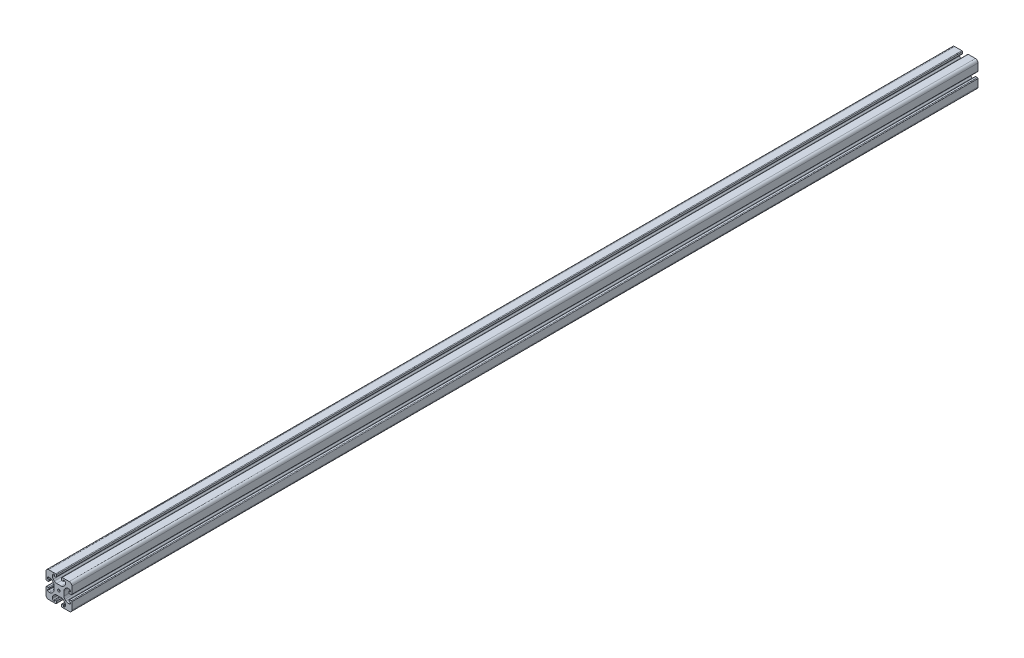
SolidWorks part; units mm, degrees
material "氧化铝"
ref_plane "前视基准面" through (0, 0, 0) normal (0, 0, 1) x (1, 0, 0)
ref_plane "上视基准面" through (0, 0, 0) normal (0, 1, 0) x (1, 0, 0)
ref_plane "右视基准面" through (0, 0, 0) normal (1, 0, 0) x (0, 0, -1)
sketch "Model" plane through (0, 0, 0) normal (0, 0, 1) x (1, 0, 0)
  line L2 (3038.626, 1538.5549) -> (3045.7412, 1538.5549)
  line L3 (3037.1836, 1526.3047) -> (3026.1835, 1526.3048)
  line L4 (3032.1835, 1530.8048) -> (3032.1835, 1532.1123)
  line L5 (3033.6481, 1535.6478) -> (3035.0903, 1537.0902)
  line L6 (3034.7336, 1528.3048) -> (3034.6836, 1528.3048)
  line L7 (3037.1836, 1530.8048) -> (3035.6835, 1530.8048)
  line L8 (3035.1835, 1528.7549) -> (3035.1835, 1530.3049)
  line L9 (3022.1835, 1530.305) -> (3022.1835, 1541.3049)
  line L10 (3038.1835, 1565.3049) -> (3038.1835, 1562.8049)
  line L11 (3031.5267, 1554.8404) -> (3032.9691, 1553.398)
  line L12 (3026.6837, 1556.305) -> (3027.9911, 1556.305)
  line L13 (3026.1835, 1553.305) -> (3024.6335, 1553.305)
  line L14 (3024.1836, 1553.7549) -> (3024.1836, 1553.8049)
  line L15 (3026.6837, 1551.3049) -> (3026.6837, 1552.805)
  line L16 (3023.1837, 1550.305) -> (3025.6835, 1550.305)
  line L17 (3022.1835, 1562.3048) -> (3022.1835, 1551.3049)
  line L18 (3023.1837, 1542.3048) -> (3025.6835, 1542.3048)
  line L19 (3026.6837, 1541.3049) -> (3026.6837, 1539.8048)
  line L20 (3024.1836, 1538.8549) -> (3024.1836, 1538.8048)
  line L21 (3026.1835, 1539.3048) -> (3024.6335, 1539.3048)
  line L22 (3026.6837, 1536.3048) -> (3027.9911, 1536.3048)
  line L23 (3031.5267, 1537.7694) -> (3032.9691, 1539.2118)
  line L24 (3035.1835, 1563.8549) -> (3035.1835, 1562.3049)
  line L25 (3037.1836, 1561.805) -> (3035.6835, 1561.805)
  line L26 (3034.7336, 1564.305) -> (3034.6836, 1564.305)
  line L27 (3038.1835, 1527.3048) -> (3038.1835, 1529.8049)
  line L28 (3049.9338, 1549.8624) -> (3049.9338, 1542.7473)
  line L29 (3047.1836, 1566.3051) -> (3058.1838, 1566.305)
  line L30 (3052.1837, 1561.805) -> (3052.1837, 1560.4975)
  line L31 (3050.7191, 1556.962) -> (3049.2769, 1555.5195)
  line L32 (3033.6481, 1556.962) -> (3035.0903, 1555.5195)
  line L33 (3032.1835, 1561.805) -> (3032.1835, 1560.4975)
  line L34 (3046.1837, 1527.3048) -> (3046.1837, 1529.8049)
  line L35 (3049.6336, 1564.305) -> (3049.6837, 1564.305)
  line L36 (3047.1836, 1561.805) -> (3048.6837, 1561.805)
  line L37 (3049.1837, 1563.8549) -> (3049.1837, 1562.3049)
  line L38 (3052.8406, 1537.7694) -> (3051.3981, 1539.2118)
  line L39 (3057.6836, 1536.3048) -> (3056.3761, 1536.3048)
  line L40 (3058.1838, 1539.3048) -> (3059.7337, 1539.3048)
  line L41 (3060.1836, 1538.8549) -> (3060.1836, 1538.8048)
  line L42 (3057.6836, 1541.3049) -> (3057.6836, 1539.8048)
  line L43 (3061.1835, 1542.3048) -> (3058.6837, 1542.3048)
  line L44 (3037.1836, 1566.3051) -> (3026.1835, 1566.305)
  line L45 (3062.1837, 1562.3048) -> (3062.1837, 1551.3049)
  line L46 (3038.626, 1554.0549) -> (3045.7412, 1554.0549)
  line L47 (3061.1835, 1550.305) -> (3058.6837, 1550.305)
  line L48 (3057.6836, 1551.3049) -> (3057.6836, 1552.805)
  line L49 (3060.1836, 1553.7549) -> (3060.1836, 1553.8049)
  line L50 (3058.1838, 1553.305) -> (3059.7337, 1553.305)
  line L51 (3057.6836, 1556.305) -> (3056.3761, 1556.305)
  line L52 (3034.4335, 1549.8624) -> (3034.4335, 1542.7473)
  line L53 (3052.8406, 1554.8404) -> (3051.3981, 1553.398)
  line L54 (3046.1837, 1565.3049) -> (3046.1837, 1562.8049)
  line L55 (3062.1837, 1530.305) -> (3062.1837, 1541.3049)
  line L56 (3049.1837, 1528.7549) -> (3049.1837, 1530.3049)
  line L57 (3047.1836, 1530.8048) -> (3048.6837, 1530.8048)
  line L58 (3049.6336, 1528.3048) -> (3049.6837, 1528.3048)
  line L59 (3050.7191, 1535.6478) -> (3049.2769, 1537.0902)
  line L60 (3052.1837, 1530.8048) -> (3052.1837, 1532.1123)
  line L61 (3047.1836, 1526.3047) -> (3058.1838, 1526.3048)
  spline S0 degree 3 poles (3026.1835, 1526.3048) (3024.8345, 1526.3048) (3023.0907, 1527.3653) (3022.1835, 1529.3623) (3022.1835, 1530.305) knots 0 0 0 0 0.550544 1 1 1 1
  spline S1 degree 3 poles (3032.1835, 1532.1123) (3032.1835, 1532.8016) (3032.4749, 1534.0839) (3033.1746, 1535.1743) (3033.6481, 1535.6478) knots 0 0 0 0 0.510204 1 1 1 1
  spline S2 degree 3 poles (3035.0903, 1537.0902) (3035.5565, 1537.5565) (3036.6626, 1538.2661) (3037.9261, 1538.5549) (3038.626, 1538.5549) knots 0 0 0 0 0.489373 1 1 1 1
  spline S3 degree 3 poles (3038.1835, 1529.8049) (3038.1835, 1530.1088) (3037.8896, 1530.5989) (3037.4374, 1530.8048) (3037.1836, 1530.8048) knots 0 0 0 0 0.565195 1 1 1 1
  spline S4 degree 3 poles (3035.6835, 1530.8048) (3035.5526, 1530.8048) (3035.3033, 1530.6873) (3035.1835, 1530.4632) (3035.1835, 1530.3049) knots 0 0 0 0 0.482406 1 1 1 1
  spline S5 degree 3 poles (3035.1835, 1528.7549) (3035.1835, 1528.6211) (3035.0566, 1528.3999) (3034.8531, 1528.3048) (3034.7336, 1528.3048) knots 0 0 0 0 0.549542 1 1 1 1
  spline S6 degree 3 poles (3034.6836, 1528.3048) (3033.9863, 1528.3048) (3032.7434, 1528.9085) (3032.1835, 1530.0457) (3032.1835, 1530.8048) knots 0 0 0 0 0.502794 1 1 1 1
  spline S7 degree 3 poles (3022.1835, 1541.3049) (3022.1835, 1541.6421) (3022.4486, 1542.0781) (3022.9479, 1542.3048) (3023.1837, 1542.3048) knots 0 0 0 0 0.550415 1 1 1 1
  spline S8 degree 3 poles (3025.6835, 1542.3048) (3026.0194, 1542.3048) (3026.4561, 1542.0413) (3026.6837, 1541.5421) (3026.6837, 1541.3049) knots 0 0 0 0 0.548464 1 1 1 1
  spline S9 degree 3 poles (3026.6837, 1539.8048) (3026.6837, 1539.6386) (3026.5536, 1539.4195) (3026.3039, 1539.3048) (3026.1835, 1539.3048) knots 0 0 0 0 0.543008 1 1 1 1
  spline S10 degree 3 poles (3024.6335, 1539.3048) (3024.4666, 1539.3048) (3024.2778, 1539.1702) (3024.1836, 1538.9461) (3024.1836, 1538.8549) knots 0 0 0 0 0.601272 1 1 1 1
  spline S11 degree 3 poles (3024.1836, 1538.8048) (3024.1836, 1537.973) (3024.8335, 1536.8769) (3026.0817, 1536.3048) (3026.6837, 1536.3048) knots 0 0 0 0 0.543506 1 1 1 1
  spline S12 degree 3 poles (3027.9911, 1536.3048) (3028.6698, 1536.3048) (3029.9377, 1536.5775) (3031.0429, 1537.2857) (3031.5267, 1537.7694) knots 0 0 0 0 0.495307 1 1 1 1
  spline S13 degree 3 poles (3032.9691, 1539.2118) (3033.4334, 1539.6761) (3034.1274, 1540.7681) (3034.4335, 1542.0508) (3034.4335, 1542.7473) knots 0 0 0 0 0.481772 1 1 1 1
  spline S14 degree 3 poles (3037.1836, 1526.3047) (3037.4, 1526.3047) (3037.8987, 1526.5226) (3038.1835, 1526.9491) (3038.1835, 1527.3048) knots 0 0 0 0 0.421049 1 1 1 1
  spline S15 degree 3 poles (3058.1838, 1566.305) (3059.5327, 1566.305) (3061.2765, 1565.2445) (3062.1837, 1563.2474) (3062.1837, 1562.3048) knots 0 0 0 0 0.550544 1 1 1 1
  spline S16 degree 3 poles (3052.1837, 1560.4975) (3052.1837, 1559.8082) (3051.8923, 1558.5259) (3051.1926, 1557.4355) (3050.7191, 1556.962) knots 0 0 0 0 0.510204 1 1 1 1
  spline S17 degree 3 poles (3049.2769, 1555.5195) (3048.8108, 1555.0533) (3047.7046, 1554.3437) (3046.4411, 1554.0549) (3045.7412, 1554.0549) knots 0 0 0 0 0.489373 1 1 1 1
  spline S18 degree 3 poles (3046.1837, 1562.8049) (3046.1837, 1562.501) (3046.4776, 1562.0109) (3046.9298, 1561.805) (3047.1836, 1561.805) knots 0 0 0 0 0.565195 1 1 1 1
  spline S19 degree 3 poles (3037.1836, 1566.3051) (3037.4, 1566.3051) (3037.8987, 1566.0872) (3038.1835, 1565.6607) (3038.1835, 1565.3049) knots 0 0 0 0 0.421049 1 1 1 1
  spline S20 degree 3 poles (3048.6837, 1561.805) (3048.8146, 1561.805) (3049.0639, 1561.9225) (3049.1837, 1562.1466) (3049.1837, 1562.3049) knots 0 0 0 0 0.482406 1 1 1 1
  spline S21 degree 3 poles (3032.9691, 1553.398) (3033.4334, 1552.9336) (3034.1274, 1551.8416) (3034.4335, 1550.559) (3034.4335, 1549.8624) knots 0 0 0 0 0.481772 1 1 1 1
  spline S22 degree 3 poles (3027.9911, 1556.305) (3028.6698, 1556.305) (3029.9377, 1556.0322) (3031.0429, 1555.3241) (3031.5267, 1554.8404) knots 0 0 0 0 0.495307 1 1 1 1
  spline S23 degree 3 poles (3024.1836, 1553.8049) (3024.1836, 1554.6368) (3024.8335, 1555.7328) (3026.0817, 1556.305) (3026.6837, 1556.305) knots 0 0 0 0 0.543506 1 1 1 1
  spline S24 degree 3 poles (3024.6335, 1553.305) (3024.4666, 1553.305) (3024.2778, 1553.4396) (3024.1836, 1553.6637) (3024.1836, 1553.7549) knots 0 0 0 0 0.601272 1 1 1 1
  spline S25 degree 3 poles (3026.6837, 1552.805) (3026.6837, 1552.9712) (3026.5536, 1553.1903) (3026.3039, 1553.305) (3026.1835, 1553.305) knots 0 0 0 0 0.543008 1 1 1 1
  spline S26 degree 3 poles (3025.6835, 1550.305) (3026.0194, 1550.305) (3026.4561, 1550.5685) (3026.6837, 1551.0677) (3026.6837, 1551.3049) knots 0 0 0 0 0.548464 1 1 1 1
  spline S27 degree 3 poles (3022.1835, 1551.3049) (3022.1835, 1550.9677) (3022.4486, 1550.5317) (3022.9479, 1550.305) (3023.1837, 1550.305) knots 0 0 0 0 0.550415 1 1 1 1
  spline S28 degree 3 poles (3049.1837, 1563.8549) (3049.1837, 1563.9886) (3049.3106, 1564.2099) (3049.5141, 1564.305) (3049.6336, 1564.305) knots 0 0 0 0 0.549542 1 1 1 1
  spline S29 degree 3 poles (3049.6837, 1564.305) (3050.3809, 1564.305) (3051.6238, 1563.7012) (3052.1837, 1562.5641) (3052.1837, 1561.805) knots 0 0 0 0 0.502794 1 1 1 1
  spline S30 degree 3 poles (3062.1837, 1551.3049) (3062.1837, 1550.9677) (3061.9186, 1550.5317) (3061.4193, 1550.305) (3061.1835, 1550.305) knots 0 0 0 0 0.550415 1 1 1 1
  spline S31 degree 3 poles (3058.6837, 1550.305) (3058.3478, 1550.305) (3057.9111, 1550.5685) (3057.6836, 1551.0677) (3057.6836, 1551.3049) knots 0 0 0 0 0.548464 1 1 1 1
  spline S32 degree 3 poles (3057.6836, 1552.805) (3057.6836, 1552.9712) (3057.8136, 1553.1903) (3058.0633, 1553.305) (3058.1838, 1553.305) knots 0 0 0 0 0.543008 1 1 1 1
  spline S33 degree 3 poles (3059.7337, 1553.305) (3059.9006, 1553.305) (3060.0894, 1553.4396) (3060.1836, 1553.6637) (3060.1836, 1553.7549) knots 0 0 0 0 0.601272 1 1 1 1
  spline S34 degree 3 poles (3060.1836, 1553.8049) (3060.1836, 1554.6368) (3059.5337, 1555.7328) (3058.2856, 1556.305) (3057.6836, 1556.305) knots 0 0 0 0 0.543506 1 1 1 1
  spline S35 degree 3 poles (3056.3761, 1556.305) (3055.6974, 1556.305) (3054.4295, 1556.0322) (3053.3243, 1555.3241) (3052.8406, 1554.8404) knots 0 0 0 0 0.495307 1 1 1 1
  spline S36 degree 3 poles (3051.3981, 1553.398) (3050.9338, 1552.9336) (3050.2398, 1551.8416) (3049.9338, 1550.559) (3049.9338, 1549.8624) knots 0 0 0 0 0.481772 1 1 1 1
  spline S37 degree 3 poles (3047.1836, 1566.3051) (3046.9672, 1566.3051) (3046.4685, 1566.0872) (3046.1837, 1565.6607) (3046.1837, 1565.3049) knots 0 0 0 0 0.421049 1 1 1 1
  spline S38 degree 3 poles (3034.6836, 1564.305) (3033.9863, 1564.305) (3032.7434, 1563.7012) (3032.1835, 1562.5641) (3032.1835, 1561.805) knots 0 0 0 0 0.502794 1 1 1 1
  spline S39 degree 3 poles (3035.1835, 1563.8549) (3035.1835, 1563.9886) (3035.0566, 1564.2099) (3034.8531, 1564.305) (3034.7336, 1564.305) knots 0 0 0 0 0.549542 1 1 1 1
  spline S40 degree 3 poles (3035.6835, 1561.805) (3035.5526, 1561.805) (3035.3033, 1561.9225) (3035.1835, 1562.1466) (3035.1835, 1562.3049) knots 0 0 0 0 0.482406 1 1 1 1
  spline S41 degree 3 poles (3038.1835, 1562.8049) (3038.1835, 1562.501) (3037.8896, 1562.0109) (3037.4374, 1561.805) (3037.1836, 1561.805) knots 0 0 0 0 0.565195 1 1 1 1
  spline S42 degree 3 poles (3047.1836, 1526.3047) (3046.9672, 1526.3047) (3046.4685, 1526.5226) (3046.1837, 1526.9491) (3046.1837, 1527.3048) knots 0 0 0 0 0.421049 1 1 1 1
  spline S43 degree 3 poles (3051.3981, 1539.2118) (3050.9338, 1539.6761) (3050.2398, 1540.7681) (3049.9338, 1542.0508) (3049.9338, 1542.7473) knots 0 0 0 0 0.481772 1 1 1 1
  spline S44 degree 3 poles (3056.3761, 1536.3048) (3055.6974, 1536.3048) (3054.4295, 1536.5775) (3053.3243, 1537.2857) (3052.8406, 1537.7694) knots 0 0 0 0 0.495307 1 1 1 1
  spline S45 degree 3 poles (3060.1836, 1538.8048) (3060.1836, 1537.973) (3059.5337, 1536.8769) (3058.2856, 1536.3048) (3057.6836, 1536.3048) knots 0 0 0 0 0.543506 1 1 1 1
  spline S46 degree 3 poles (3059.7337, 1539.3048) (3059.9006, 1539.3048) (3060.0894, 1539.1702) (3060.1836, 1538.9461) (3060.1836, 1538.8549) knots 0 0 0 0 0.601272 1 1 1 1
  spline S47 degree 3 poles (3057.6836, 1539.8048) (3057.6836, 1539.6386) (3057.8136, 1539.4195) (3058.0633, 1539.3048) (3058.1838, 1539.3048) knots 0 0 0 0 0.543008 1 1 1 1
  spline S48 degree 3 poles (3058.6837, 1542.3048) (3058.3478, 1542.3048) (3057.9111, 1542.0413) (3057.6836, 1541.5421) (3057.6836, 1541.3049) knots 0 0 0 0 0.548464 1 1 1 1
  spline S49 degree 3 poles (3062.1837, 1541.3049) (3062.1837, 1541.6421) (3061.9186, 1542.0781) (3061.4193, 1542.3048) (3061.1835, 1542.3048) knots 0 0 0 0 0.550415 1 1 1 1
  spline S50 degree 3 poles (3049.6837, 1528.3048) (3050.3809, 1528.3048) (3051.6238, 1528.9085) (3052.1837, 1530.0457) (3052.1837, 1530.8048) knots 0 0 0 0 0.502794 1 1 1 1
  spline S51 degree 3 poles (3035.0903, 1555.5195) (3035.5565, 1555.0533) (3036.6626, 1554.3437) (3037.9261, 1554.0549) (3038.626, 1554.0549) knots 0 0 0 0 0.489373 1 1 1 1
  spline S52 degree 3 poles (3032.1835, 1560.4975) (3032.1835, 1559.8082) (3032.4749, 1558.5259) (3033.1746, 1557.4355) (3033.6481, 1556.962) knots 0 0 0 0 0.510204 1 1 1 1
  spline S53 degree 3 poles (3049.1837, 1528.7549) (3049.1837, 1528.6211) (3049.3106, 1528.3999) (3049.5141, 1528.3048) (3049.6336, 1528.3048) knots 0 0 0 0 0.549542 1 1 1 1
  spline S54 degree 3 poles (3048.6837, 1530.8048) (3048.8146, 1530.8048) (3049.0639, 1530.6873) (3049.1837, 1530.4632) (3049.1837, 1530.3049) knots 0 0 0 0 0.482406 1 1 1 1
  spline S55 degree 3 poles (3046.1837, 1529.8049) (3046.1837, 1530.1088) (3046.4776, 1530.5989) (3046.9298, 1530.8048) (3047.1836, 1530.8048) knots 0 0 0 0 0.565195 1 1 1 1
  spline S56 degree 3 poles (3049.2769, 1537.0902) (3048.8108, 1537.5565) (3047.7046, 1538.2661) (3046.4411, 1538.5549) (3045.7412, 1538.5549) knots 0 0 0 0 0.489373 1 1 1 1
  spline S57 degree 3 poles (3052.1837, 1532.1123) (3052.1837, 1532.8016) (3051.8923, 1534.0839) (3051.1926, 1535.1743) (3050.7191, 1535.6478) knots 0 0 0 0 0.510204 1 1 1 1
  spline S58 degree 3 poles (3058.1838, 1526.3048) (3059.5327, 1526.3048) (3061.2765, 1527.3653) (3062.1837, 1529.3623) (3062.1837, 1530.305) knots 0 0 0 0 0.550544 1 1 1 1
  spline S68 degree 3 poles (3026.1835, 1566.305) (3024.8345, 1566.305) (3023.0907, 1565.2445) (3022.1835, 1563.2474) (3022.1835, 1562.3048) knots 0 0 0 0 0.550544 1 1 1 1
extrude "凸台-拉伸3" add sketch "Model" along normal blind 1400 contours S22 L11 S21 L52 S13 L23 S12 L22 S11 L20 S10 L21 S9 L19 S8 L18 S7 L9 S0 L3 S14 L27 S3 L7 S4 L8 S5 L6 S6 L4 S1 L5 S2 L2 S56 L59 S57 L60 S50 L58 S53 L56 S54 L57 S55 L34 S42 L61 S58 L55 S49 L43 S48 L42 S47 L40 S46 L41 S45 L39 S44 L38 S43 L28 S36 L53 S35 L51 S34 L49 S33 L50 S32 L48 S31 L47 S30 L45 S15 L29 S37 L54 S18 L36 S20 L37 S28 L35 S29 L30 S16 L31 S17 L46 S51 L32 S52 L33 S38 L26 S39 L24 S40 L25 S41 L10 S19 L44 S68 L17 S27 L16 S26 L15 S25 L13 S24 L14 S23 L12
sketch "草图1" plane through (3034.4335, 0, 0) normal (-1, 0, 0) x (0, 0, 1)
  line L0 (1400, 1549.8624) -> (1400, 1542.7473) construction
  line L1 (0, 1549.8624) -> (0, 1542.7473) construction
  point P0 (1360, 1546.3049)
  point P3 (20, 1546.3049)
  dimension "D1" = 40
  dimension "D2" = 20
hole_wizard "M5 螺纹孔1" positions "草图2" profile "草图3" tap size "M5" standard "GB" end condition through all
sketch "草图2" plane through (3034.4335, 0, 0) normal (-1, 0, 0) x (0, 0, 1)
  point P0 (1360, 1546.3049)
  point P4 (20, 1546.3049)
sketch "草图3" plane through (3034.4335, 1546.3049, 1360) normal (0, 1, 0) x (0, 0, 1)
  line L0 (0, 0) -> (0, 27.7503)
  line L1 (0, 27.7503) -> (2.1, 27.7503)
  line L2 (2.1, 27.7503) -> (2.1, 0)
  line L5 (2.1, 0) -> (0, 0)
  line L11 (0, -6.35) -> (0, 107.95) construction
  dimension "通孔螺纹孔钻头直径" = 4.2
  dimension "通孔螺纹孔钻头深度" = 27.7503
cosmetic thread "孔螺蚊线1" parameters "D2"=5
cosmetic thread "孔螺蚊线2" parameters "D2"=5
sketch "草图4" plane through (0, 1554.0549, 0) normal (0, 1, 0) x (1, 0, 0)
  line L0 (3038.626, -1400) -> (3045.7412, -1400) construction
  line L1 (3038.626, 0) -> (3045.7412, 0) construction
  point P0 (3042.1836, -1360)
  point P3 (3042.1836, -1400)
  point P4 (3042.1836, -20)
  dimension "D1" = 40
  dimension "D2" = 20
hole_wizard "M5 螺纹孔2" positions "草图5" profile "草图6" tap size "M5" standard "GB" end condition through all
sketch "草图5" plane through (0, 1554.0549, 0) normal (0, 1, 0) x (1, 0, 0)
  point P0 (3042.1836, -20)
  point P3 (3042.1836, -1360)
sketch "草图6" plane through (3042.1836, 1554.0549, 20) normal (1, 0, 0) x (0, 0, 1)
  line L0 (0, 0) -> (0, 27.7503)
  line L1 (0, 27.7503) -> (2.1, 27.7503)
  line L2 (2.1, 27.7503) -> (2.1, 0)
  line L5 (2.1, 0) -> (0, 0)
  line L11 (0, -6.35) -> (0, 107.95) construction
  dimension "通孔螺纹孔钻头直径" = 4.2
  dimension "通孔螺纹孔钻头深度" = 27.7503
cosmetic thread "孔螺蚊线3" parameters "D2"=5
cosmetic thread "孔螺蚊线4" parameters "D2"=5
sketch "草图7" plane through (0, 0, 1400) normal (0, 0, 1) x (1, 0, 0)
  circle A0 centre (3042.1836, 1546.3049) radius 2
extrude "切除-拉伸1" cut sketch "草图7" against normal blind 2
sketch "草图8" plane through (3049.9338, 0, 0) normal (1, 0, 0) x (0, 0, -1)
  line L0 (-1400, 1549.8624) -> (-1400, 1542.7473) construction
  point P0 (-1045, 1546.3049)
  point P3 (-1400, 1546.3049)
  point P4 (-587.5, 1546.3049)
  point P5 (-587.5, 1546.3049)
  point P6 (-222.5, 1546.3049)
  dimension "D1" = 355
  dimension "D2" = 812.5
  dimension "D3" = 1177.5
hole_wizard "M5 螺纹孔3" positions "草图9" profile "草图10" tap size "M5" standard "GB" end condition through all
sketch "草图9" plane through (3049.9338, 0, 0) normal (1, 0, 0) x (0, 0, -1)
  point P0 (-1045, 1546.3049)
  point P3 (-587.5, 1546.3049)
  point P6 (-222.5, 1546.3049)
sketch "草图10" plane through (3049.9338, 1546.3049, 1045) normal (0, 1, 0) x (0, 0, -1)
  line L0 (0, 0) -> (0, 27.7503)
  line L1 (0, 27.7503) -> (2.1, 27.7503)
  line L2 (2.1, 27.7503) -> (2.1, 0)
  line L5 (2.1, 0) -> (0, 0)
  line L11 (0, -6.35) -> (0, 107.95) construction
  dimension "通孔螺纹孔钻头直径" = 4.2
  dimension "通孔螺纹孔钻头深度" = 27.7503
cosmetic thread "孔螺蚊线5" parameters "D2"=5
cosmetic thread "孔螺蚊线6" parameters "D2"=5
cosmetic thread "孔螺蚊线7" parameters "D2"=5
sketch "草图11" plane through (0, 1554.0549, 0) normal (0, 1, 0) x (1, 0, 0)
  line L0 (3038.626, -1400) -> (3045.7412, -1400) construction
  point P0 (3042.1836, -1045)
  point P3 (3042.1836, -587.5)
  point P4 (3042.1836, -222.5)
  dimension "D1" = 355
  dimension "D2" = 812.5
  dimension "D3" = 1177.5
hole_wizard "M5 螺纹孔4" positions "草图12" profile "草图13" tap size "M5" standard "GB" end condition through all
sketch "草图12" plane through (0, 1554.0549, 0) normal (0, 1, 0) x (1, 0, 0)
  point P0 (3042.1836, -222.5)
  point P3 (3042.1836, -587.5)
  point P6 (3042.1836, -1045)
sketch "草图13" plane through (3042.1836, 1554.0549, 222.5) normal (1, 0, 0) x (0, 0, 1)
  line L0 (0, 0) -> (0, 27.7503)
  line L1 (0, 27.7503) -> (2.1, 27.7503)
  line L2 (2.1, 27.7503) -> (2.1, 0)
  line L5 (2.1, 0) -> (0, 0)
  line L11 (0, -6.35) -> (0, 107.95) construction
  dimension "通孔螺纹孔钻头直径" = 4.2
  dimension "通孔螺纹孔钻头深度" = 27.7503
cosmetic thread "孔螺蚊线8" parameters "D2"=5
cosmetic thread "孔螺蚊线9" parameters "D2"=5
cosmetic thread "孔螺蚊线10" parameters "D2"=5
